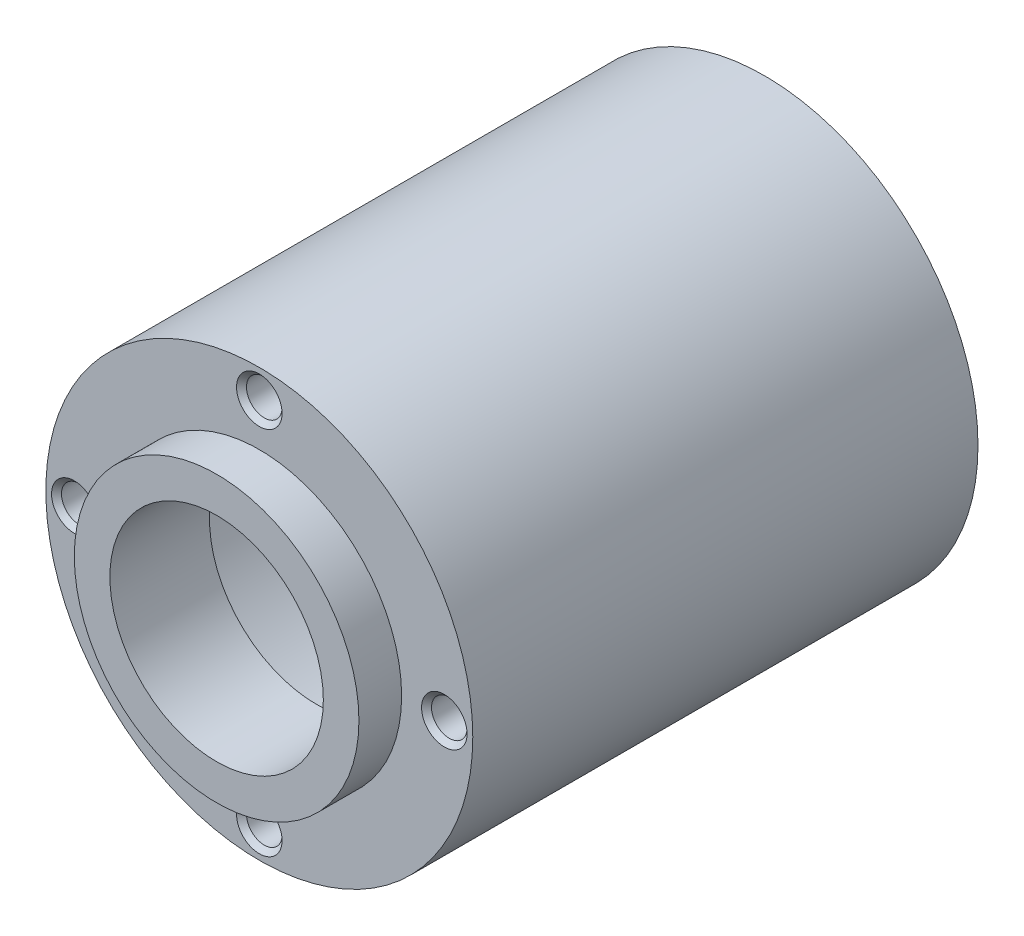
SolidWorks part; units mm, degrees
material "Alloy Steel"
ref_plane "Front Plane" through (0, 0, 0) normal (0, 0, 1) x (1, 0, 0)
ref_plane "Top Plane" through (0, 0, 0) normal (0, 1, 0) x (1, 0, 0)
ref_plane "Right Plane" through (0, 0, 0) normal (1, 0, 0) x (0, 0, -1)
sketch "Sketch1" plane through (0, 0, 0) normal (0, 0, 1) x (1, 0, 0)
  circle A0 centre (0, 0) radius 15
  dimension "D1" = 30
extrude "Boss-Extrude1" add sketch "Sketch1" against normal blind 35.5
sketch "Sketch2" plane through (0, 0, -35.5) normal (0, 0, 1) x (1, 0, 0)
  circle A0 centre (0, 0) radius 14.2
  circle A1 centre (0, 0) radius 15 construction
  dimension "D1" = 0.8
extrude "Cut-Extrude1" cut sketch "Sketch2" along normal offset from surface (31.5 mm away) 4 up to face at (15, 0, 0)
sketch "Sketch3" plane through (0, 0, 0) normal (0, 0, -1) x (-1, 0, 0)
  circle A0 centre (0, 0) radius 7.5
  point P2 (-0.3934, 4.6089)
  point P3 (0, 0)
  dimension "D1" = 15
extrude "Cut-Extrude2" cut sketch "Sketch3" along normal through all
hole_wizard "M3x0.5 Tapped Hole1" positions "Sketch6" profile "Sketch7" tap size "M3x0.5" standard "ANSI Metric" end condition through all
sketch "Sketch6" plane through (0, 0, 0) normal (0, 0, -1) x (-1, 0, 0)
  line L0 (-13, 0) -> (0, 0) construction
  point P0 (-13, 0)
  dimension "D1" = 13
sketch "Sketch7" plane through (13, 0, 0) normal (1, 0, 0) x (0, -1, 0)
  line L0 (0, 0) -> (0, 35.5)
  line L1 (0, 35.5) -> (1.25, 35.5)
  line L2 (1.25, 35.5) -> (1.25, 0.35)
  line L3 (1.25, 0.35) -> (1.6, 0)
  line L5 (1.6, 0) -> (0, 0)
  line L6 (-1.25, 0.35) -> (-1.6, 0) construction
  line L11 (0, -6.35) -> (0, 107.95) construction
  dimension "Thread Major Dia." = 2.5
  dimension "Thru Tap Drill Depth" = 35.5
  dimension "Near C'Sink Dia." = 3.2
  dimension "Near C'Sink Angle" = 90
pattern_circular "CirPattern2" count 4 over 360 about axis through (0, 0, 0) along (0, 0, 1) of "M3x0.5 Tapped Hole1"
sketch "Sketch8" plane through (0, 0, 0) normal (0, 0, 1) x (1, 0, 0)
  circle A0 centre (0, 0) radius 10
  circle A1 centre (0, 0) radius 7.5
  dimension "D1" = 20
extrude "Boss-Extrude2" add sketch "Sketch8" along normal blind 3
